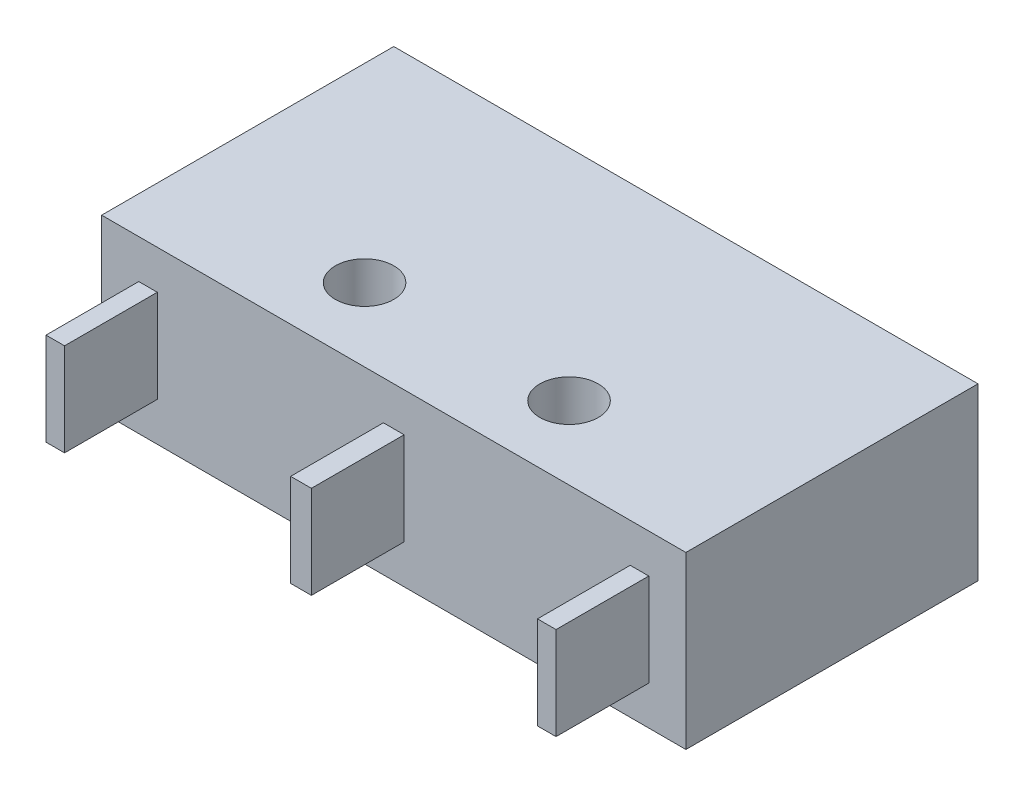
SolidWorks part; units mm, degrees
ref_plane "Plan de face" through (0, 0, 0) normal (0, 0, 1) x (1, 0, 0)
ref_plane "Plan de dessus" through (0, 0, 0) normal (0, 1, 0) x (1, 0, 0)
ref_plane "Plan de droite" through (0, 0, 0) normal (1, 0, 0) x (0, 0, -1)
sketch "Esquisse1" plane through (0, 0, 0) normal (0, 1, 0) x (1, 0, 0)
  line L1 (-10, 5) -> (10, 5)
  line L2 (-10, 5) -> (-10, -5)
  line L3 (-10, -5) -> (10, -5)
  line L4 (10, 5) -> (10, -5)
  line L5 (-10, 5) -> (10, -5) construction
  line L6 (-10, -5) -> (10, 5) construction
  point P0 (0, 0)
  dimension "D1" = 10
  dimension "D2" = 20
extrude "Boss.-Extru.1" add sketch "Esquisse1" along normal blind 5.842
ref_plane "Plan1" through (0, 2.921, 0) normal (0, -1, 0) x (-1, 0, 0)
sketch "Esquisse2" plane through (0, 2.921, 0) normal (0, -1, 0) x (-1, 0, 0)
  line L0 (10, -5) -> (8.73, -5) construction
  line L1 (10, -5) -> (-10, -5) construction
  line L2 (8.73, -5) -> (8.095, -5)
  line L3 (8.095, -5) -> (8.095, -8.175)
  line L4 (8.73, -5) -> (8.73, -8.175)
  line L5 (8.095, -8.175) -> (8.73, -8.175)
  line L6 (0, -5) -> (0, -8.4982) construction
  line L7 (-8.73, -5) -> (-8.095, -5)
  line L8 (-8.095, -8.175) -> (-8.73, -8.175)
  line L9 (-8.73, -5) -> (-8.73, -8.175)
  line L10 (-8.095, -5) -> (-8.095, -8.175)
  line L11 (-0.3549, -5) -> (0.3549, -5)
  line L12 (0.3549, -8.175) -> (-0.3549, -8.175)
  line L13 (-0.3549, -5) -> (-0.3549, -8.175)
  line L14 (0.3549, -5) -> (0.3549, -8.175)
  point P19 (0, -5)
  dimension "D1" = 1.27
  dimension "D2" = 0.635
  dimension "D3" = 3.175
  dimension "D4" = 3.175
extrude "Boss.-Extru.3" add sketch "Esquisse2" along normal mid plane 3.175
sketch "Esquisse3" plane through (0, 0, 0) normal (0, -1, 0) x (1, 0, 0)
  line L0 (0, 5) -> (0, 2.5) construction
  line L1 (-0.3549, 5) -> (0.3549, 5) construction
  line L2 (0, 2.5) -> (3.5, 2.5) construction
  circle A0 centre (3.5, 2.5) radius 1
  circle A1 centre (-3.5, 2.5) radius 1
  dimension "D3" = 2
  dimension "D1" = 2.5
  dimension "D2" = 3.5
extrude "Enlèv. mat.-Extru.1" cut sketch "Esquisse3" against normal through all
